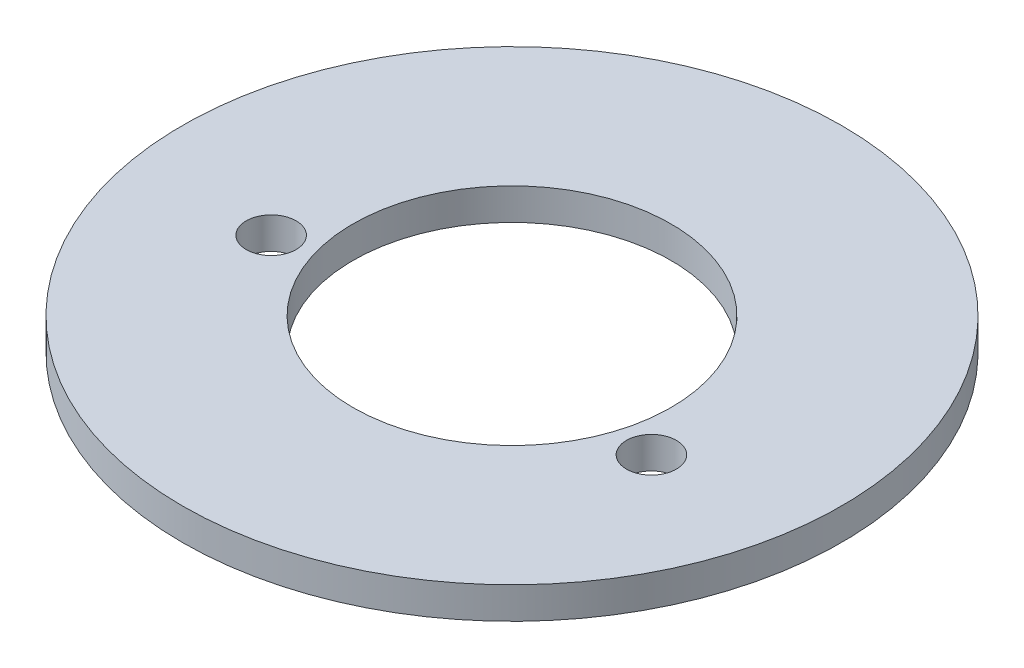
SolidWorks part; units mm, degrees
ref_plane "Front Plane" through (0, 0, 0) normal (0, 0, 1) x (1, 0, 0)
ref_plane "Top Plane" through (0, 0, 0) normal (0, 1, 0) x (1, 0, 0)
ref_plane "Right Plane" through (0, 0, 0) normal (1, 0, 0) x (0, 0, -1)
sketch "Sketch1" plane through (0, 0, 0) normal (0, 1, 0) x (1, 0, 0)
  circle A0 centre (0, 0) radius 66.04
  dimension "D1" = 132.08
extrude "Boss-Extrude1" add sketch "Sketch1" along normal blind 6.35
sketch "Sketch2" plane through (0, 6.35, 0) normal (0, 1, 0) x (1, 0, 0)
  circle A0 centre (0, 0) radius 31.877
  dimension "D1" = 63.754
extrude "Cut-Extrude1" cut sketch "Sketch2" against normal blind 6.35
sketch "Sketch3" plane through (0, 6.35, 0) normal (0, 1, 0) x (1, 0, 0)
  line L0 (-38.1, -10.16) -> (38.1, -10.16) construction
  circle A0 centre (38.1, -10.16) radius 5
  circle A1 centre (-38.1, -10.16) radius 5
  dimension "D2" = 10
  dimension "D3" = 10
  dimension "D1" = 38.1
  dimension "D4" = 38.1
  dimension "D5" = 10.16
extrude "Cut-Extrude2" cut sketch "Sketch3" against normal up to vertex (6.35 mm away) up to point (0, 0, 0)
